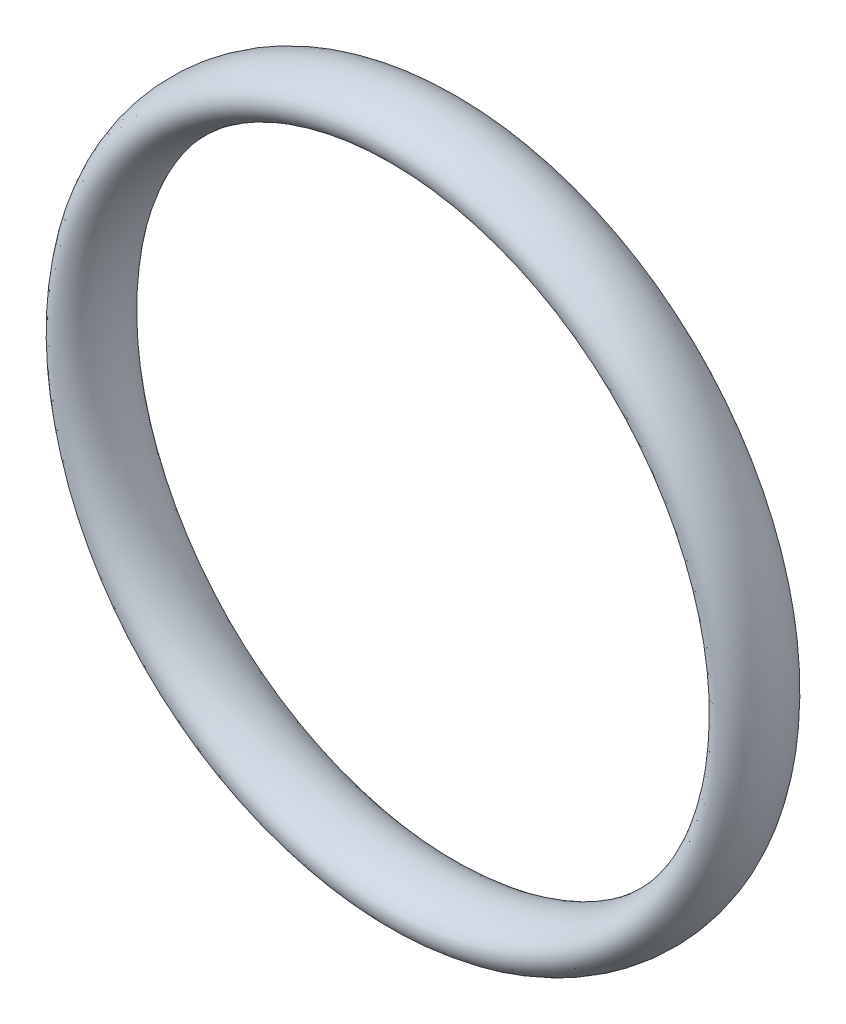
SolidWorks part; units mm, degrees
ref_plane "Front Plane" through (0, 0, 0) normal (0, 0, 1) x (1, 0, 0)
ref_plane "Top Plane" through (0, 0, 0) normal (0, 1, 0) x (1, 0, 0)
ref_plane "Right Plane" through (0, 0, 0) normal (1, 0, 0) x (0, 0, -1)
sketch "Sketch1" plane through (0, 0, 0) normal (1, 0, 0) x (0, 0, -1)
  line L0 (0, 0) -> (0, 17.25) construction
  line L1 (0, 0) -> (-8.3394, 0) construction
  ellipse E0 centre (0, 17.25) end of major axis (-2, 17.25) minor radius 1.25
  point P3 (0, 0)
  dimension "D1" = 17.25
  dimension "D2" = 4
  dimension "D3" = 2.5
revolve "Revolve1" add sketch "Sketch1" angle 360 about L1
